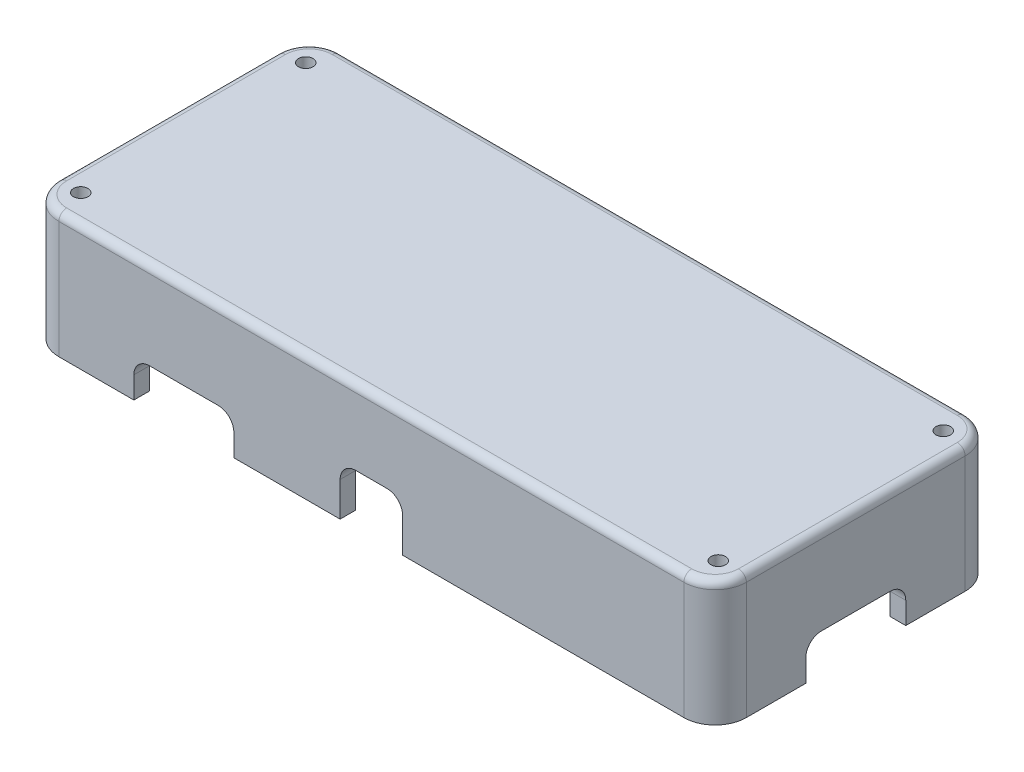
SolidWorks part; units mm, degrees
material "ABS"
ref_plane "Front Plane" through (0, 0, 0) normal (0, 0, 1) x (1, 0, 0)
ref_plane "Top Plane" through (0, 0, 0) normal (0, 1, 0) x (1, 0, 0)
ref_plane "Right Plane" through (0, 0, 0) normal (1, 0, 0) x (0, 0, -1)
sketch "Sketch1" plane through (0, 0, 0) normal (0, 1, 0) x (1, 0, 0)
  line L1 (-69.85, -28.575) -> (69.85, -28.575)
  line L2 (-69.85, -28.575) -> (-69.85, 28.575)
  line L3 (-69.85, 28.575) -> (69.85, 28.575)
  line L4 (69.85, -28.575) -> (69.85, 28.575)
  line L5 (-69.85, -28.575) -> (69.85, 28.575) construction
  line L6 (-69.85, 28.575) -> (69.85, -28.575) construction
  point P0 (0, 0)
  dimension "D1" = 139.7
  dimension "D2" = 57.15
extrude "Boss-Extrude1" add sketch "Sketch1" along normal blind 25.4
fillet "Fillet1" radius 6.35 4 edges at (-69.85, 12.7, -28.575) (69.85, 12.7, -28.575) (69.85, 12.7, 28.575) (-69.85, 12.7, 28.575)
sketch "Sketch2" plane through (0, 25.4, 0) normal (0, 1, 0) x (1, 0, 0)
  line L1 (-64.77, -22.86) -> (64.77, -22.86)
  line L2 (-64.77, -22.86) -> (-64.77, 22.86)
  line L3 (-64.77, 22.86) -> (64.77, 22.86)
  line L4 (64.77, -22.86) -> (64.77, 22.86)
  line L5 (-64.77, -22.86) -> (64.77, 22.86) construction
  line L6 (-64.77, 22.86) -> (64.77, -22.86) construction
  point P0 (0, 0)
  dimension "D1" = 129.54
  dimension "D2" = 45.72
sketch "Sketch5" plane through (0, 0, 0) normal (0, -1, 0) x (1, 0, 0)
  line L8 (-66.675, 22.225) -> (-66.675, -22.225)
  line L9 (-63.5, -25.4) -> (63.5, -25.4)
  line L10 (66.675, -22.225) -> (66.675, 22.225)
  line L11 (63.5, 25.4) -> (-63.5, 25.4)
  line L12 (-66.675, 25.4) -> (-66.675, -25.4)
  line L13 (-66.675, -25.4) -> (66.675, -25.4)
  line L14 (66.675, -25.4) -> (66.675, 25.4)
  line L15 (66.675, 25.4) -> (-66.675, 25.4)
  arc A8 (-66.675, -22.225) -> (-63.5, -25.4) centre (-63.5, -22.225) ccw
  arc A9 (63.5, -25.4) -> (66.675, -22.225) centre (63.5, -22.225) ccw
  arc A10 (66.675, 22.225) -> (63.5, 25.4) centre (63.5, 22.225) ccw
  arc A11 (-63.5, 25.4) -> (-66.675, 22.225) centre (-63.5, 22.225) ccw
  dimension "D1" = 3.175
extrude "Cut-Extrude1" cut sketch "Sketch5" against normal offset from surface (23.8125 mm away) 1.5875 up to face at (0, 25.4, 0)
fillet "Fillet5" radius 12.7 4 edges at (66.675, 11.9062, -25.4) (66.675, 11.9062, 25.4) (-66.675, 11.9062, -25.4) (-66.675, 11.9062, 25.4)
hole_wizard "#4 Clearance Hole1" positions "Sketch4" profile "Sketch3" hole size "#4" standard "Ansi Inch" end condition through all
sketch "Sketch4" plane through (0, 25.4, 0) normal (0, 1, 0) x (-1, 0, 0)
  point P1 (64.77, -22.86)
  point P4 (64.77, 22.86)
  point P7 (-64.77, -22.86)
  point P10 (-64.77, 22.86)
sketch "Sketch3" plane through (-64.77, 25.4, -22.86) normal (1, 0, 0) x (0, 0, 1)
  line L0 (0, 0) -> (0, 25.4)
  line L1 (0, 25.4) -> (1.4732, 25.4)
  line L2 (1.4732, 25.4) -> (1.4732, 0)
  line L5 (1.4732, 0) -> (0, 0)
  line L11 (0, -6.35) -> (0, 107.95) construction
  dimension "Thru Hole Dia." = 2.9464
  dimension "Thru Hole Depth" = 25.4
fillet "Fillet6" radius 1.5875 8 edges at (-67.9901, 25.4, 26.7151) (-69.85, 25.4, 0) (-67.9901, 25.4, -26.7151) (0, 25.4, -28.575) (67.9901, 25.4, -26.7151) (69.85, 25.4, 0) (67.9901, 25.4, 26.7151) (0, 25.4, 28.575)
sketch "Sketch6" plane through (69.85, 0, 0) normal (1, 0, 0) x (0, 0, -1)
  line L0 (-22.225, 0) -> (22.225, 0) construction
  line L1 (-10.16, 0) -> (10.16, 0)
  line L2 (-10.16, 0) -> (-10.16, 7.62)
  line L3 (-10.16, 7.62) -> (10.16, 7.62)
  line L4 (10.16, 0) -> (10.16, 7.62)
  line L5 (-10.16, 0) -> (10.16, 7.62) construction
  line L6 (-10.16, 7.62) -> (10.16, 0) construction
  point P0 (0, 3.81)
  dimension "D1" = 7.62
  dimension "D2" = 20.32
extrude "Cut-Extrude2" cut sketch "Sketch6" against normal up to next
sketch "Sketch7" plane through (0, 0, 28.575) normal (0, 0, 1) x (1, 0, 0)
  line L0 (-63.5, 0) -> (63.5, 0) construction
  line L1 (-48.26, 0) -> (-27.94, 0)
  line L2 (-48.26, 0) -> (-48.26, 7.62)
  line L3 (-48.26, 7.62) -> (-27.94, 7.62)
  line L4 (-27.94, 0) -> (-27.94, 7.62)
  line L5 (-48.26, 0) -> (-27.94, 7.62) construction
  line L6 (-48.26, 7.62) -> (-27.94, 0) construction
  line L7 (-69.85, 0) -> (-69.85, 23.8125) construction
  point P0 (-38.1, 3.81)
  dimension "D1" = 7.62
  dimension "D2" = 20.32
  dimension "D3" = 31.75
extrude "Cut-Extrude3" cut sketch "Sketch7" against normal up to next
sketch "Sketch8" plane through (0, 0, -28.575) normal (0, 0, -1) x (-1, 0, 0)
  line L0 (-63.5, 0) -> (63.5, 0) construction
  line L1 (-55.88, 0) -> (-43.18, 0)
  line L2 (-55.88, 0) -> (-55.88, 10.16)
  line L3 (-55.88, 10.16) -> (-43.18, 10.16)
  line L4 (-43.18, 0) -> (-43.18, 10.16)
  line L5 (-69.85, 0) -> (-69.85, 23.8125) construction
  dimension "D1" = 10.16
  dimension "D2" = 12.7
  dimension "D3" = 13.97
extrude "Cut-Extrude4" cut sketch "Sketch8" against normal up to next
fillet "Fillet7" radius 3.175 6 edges at (68.2625, 7.62, -10.16) (68.2625, 7.62, 10.16) (-27.94, 7.62, 26.9875) (-48.26, 7.62, 26.9875) (43.18, 10.16, -26.9875) (55.88, 10.16, -26.9157)
sketch "Sketch9" plane through (0, 0, 28.575) normal (0, 0, 1) x (1, 0, 0)
  line L0 (-27.94, 0) -> (63.5, 0) construction
  line L1 (-6.35, 0) -> (6.35, 0)
  line L2 (-6.35, 0) -> (-6.35, 10.16)
  line L3 (-6.35, 10.16) -> (6.35, 10.16)
  line L4 (6.35, 0) -> (6.35, 10.16)
  line L5 (-6.35, 0) -> (6.35, 10.16) construction
  line L6 (-6.35, 10.16) -> (6.35, 0) construction
  point P0 (0, 5.08)
  dimension "D1" = 10.16
  dimension "D2" = 12.7
extrude "Cut-Extrude5" cut sketch "Sketch9" against normal up to next
mirror "Mirror1" about plane through (0, 0, 0) normal (0, 0, 1) of "Cut-Extrude5"
fillet "Fillet9" radius 3.175 4 edges at (6.35, 10.16, 26.9875) (-6.35, 10.16, 26.9875) (6.35, 10.16, -26.9875) (-6.35, 10.16, -26.9875)
